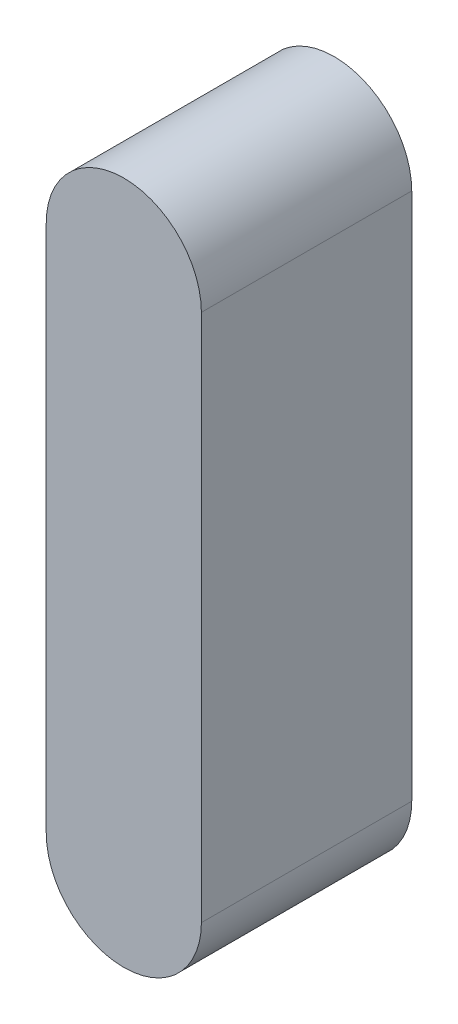
SolidWorks part; units mm, degrees
ref_plane "Front Plane" through (0, 0, 0) normal (0, 0, 1) x (1, 0, 0)
ref_plane "Top Plane" through (0, 0, 0) normal (0, 1, 0) x (1, 0, 0)
ref_plane "Right Plane" through (0, 0, 0) normal (1, 0, 0) x (0, 0, -1)
sketch "Sketch1" plane through (0, 0, 0) normal (0, 0, 1) x (1, 0, 0)
  line L0 (0, -5.025) -> (0, 5.025) construction
  line L1 (-1.475, -5.025) -> (-1.475, 5.025)
  line L2 (1.475, -5.025) -> (1.475, 5.025)
  line L3 (0, 6.5) -> (0, -6.5)
  arc A0 (-1.475, -5.025) -> (1.475, -5.025) centre (0, -5.025) ccw
  arc A1 (1.475, 5.025) -> (-1.475, 5.025) centre (0, 5.025) ccw
  point P2 (0, 0)
  dimension "D1" = 13
  dimension "D2" = 2.95
extrude "Boss-Extrude1" add sketch "Sketch1" along normal blind 4 contours L2 A1 L3 A0 | L3 A1 L1 A0
